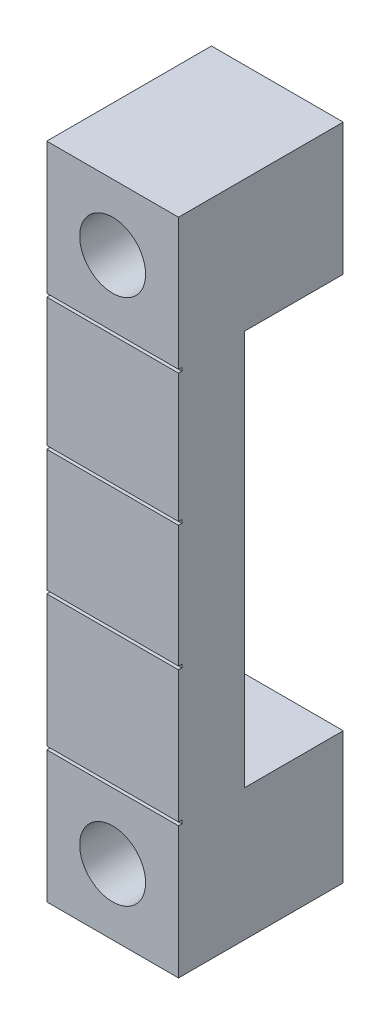
SolidWorks part; units mm, degrees
ref_plane "前视基准面" through (0, 0, 0) normal (0, 0, 1) x (1, 0, 0)
ref_plane "上视基准面" through (0, 0, 0) normal (0, 1, 0) x (1, 0, 0)
ref_plane "右视基准面" through (0, 0, 0) normal (1, 0, 0) x (0, 0, -1)
other "Configuration Table"
sketch "草图1" plane through (0, 0, 0) normal (0, 0, 1) x (1, 0, 0)
  line L1 (0, 0) -> (20, 0)
  line L2 (0, 0) -> (0, -100)
  line L3 (0, -100) -> (20, -100)
  line L4 (20, 0) -> (20, -100)
  dimension "D1" = 20
  dimension "D2" = 100
extrude "凸台-拉伸1" add sketch "草图1" along normal blind 10
sketch "草图2" plane through (0, 0, 0) normal (0, 0, -1) x (-1, 0, 0)
  line L0 (-20, -100) -> (-20, 0) construction
  line L1 (0, 0) -> (-20, 0)
  line L2 (0, 0) -> (0, -20)
  line L3 (0, -20) -> (-20, -20)
  line L4 (-20, 0) -> (-20, -20)
  line L6 (0, -100) -> (-20, -100)
  line L7 (0, -100) -> (0, -80)
  line L8 (0, -80) -> (-20, -80)
  line L9 (-20, -100) -> (-20, -80)
  dimension "D1" = 20
  dimension "D2" = 20
extrude "凸台-拉伸2" add sketch "草图2" along normal blind 15
sketch "草图3" plane through (0, 0, -15) normal (0, 0, -1) x (-1, 0, 0)
  line L0 (0, -10) -> (-50000, -10) construction
  line L1 (0, -20) -> (0, 0) construction
  line L2 (-10, 0) -> (-10, -50000) construction
  line L3 (0, 0) -> (-20, 0) construction
  line L4 (0, -90) -> (-50000, -90) construction
  line L5 (0, -100) -> (0, -80) construction
  circle A0 centre (-10, -10) radius 3
  circle A1 centre (-10, -90) radius 3
  point P4 (0, -10)
  point P9 (-10, 0)
  point P14 (0, -90)
  dimension "D1" = 6
  dimension "D2" = 6
extrude "切除-拉伸1" cut sketch "草图3" against normal through all
sketch "草图4" plane through (0, 0, 10) normal (0, 0, 1) x (1, 0, 0)
  circle A0 centre (10, -10) radius 5
  circle A1 centre (10, -90) radius 5
  dimension "D1" = 10
  dimension "D2" = 10
extrude "切除-拉伸2" cut sketch "草图4" against normal blind 15
sketch "草图5" plane through (0, 0, 10) normal (0, 0, 1) x (1, 0, 0)
  line L0 (20, -100) -> (20, 0) construction
  line L1 (0, -80) -> (20, -80)
  line L2 (0, -80) -> (0, -79.5)
  line L3 (0, -79.5) -> (20, -79.5)
  line L4 (20, -80) -> (20, -79.5)
  line L5 (0, 0) -> (0, -100) construction
  line L6 (0, -59.5) -> (20, -59.5)
  line L7 (0, -59.5) -> (0, -59)
  line L8 (0, -59) -> (20, -59)
  line L9 (20, -59.5) -> (20, -59)
  line L10 (20, 0) -> (0, 0) construction
  line L11 (0, -40) -> (20, -40)
  line L12 (0, -40) -> (0, -40.5)
  line L13 (0, -40.5) -> (20, -40.5)
  line L14 (20, -40) -> (20, -40.5)
  line L15 (0, -20.5) -> (20, -20.5)
  line L16 (0, -20.5) -> (0, -20)
  line L17 (0, -20) -> (20, -20)
  line L18 (20, -20.5) -> (20, -20)
  line L19 (0, -100) -> (20, -100) construction
  dimension "D1" = 0.5
  dimension "D2" = 20
  dimension "D3" = 20
  dimension "D4" = 0.5
  dimension "D5" = 0.5
  dimension "D6" = 20
  dimension "D7" = 20
  dimension "D8" = 0.5
extrude "切除-拉伸3" cut sketch "草图5" against normal blind 0.5
